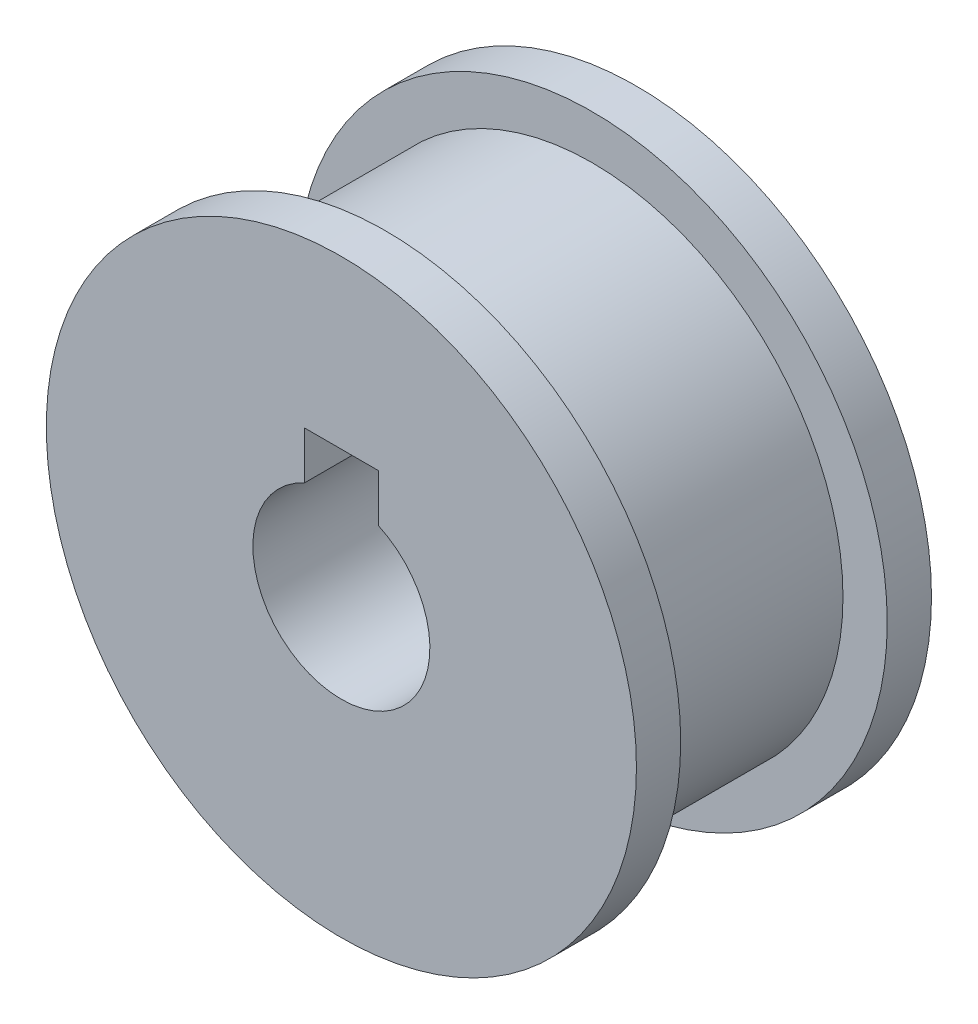
SolidWorks part; units mm, degrees
ref_plane "前视基准面" through (0, 0, 0) normal (0, 0, 1) x (1, 0, 0)
ref_plane "上视基准面" through (0, 0, 0) normal (0, 1, 0) x (1, 0, 0)
ref_plane "右视基准面" through (0, 0, 0) normal (1, 0, 0) x (0, 0, -1)
other "Configuration Table"
sketch "草图1" plane through (0, 0, 0) normal (0, 0, 1) x (1, 0, 0)
  circle A0 centre (0, 0) radius 17
  dimension "D1" = 34
extrude "凸台-拉伸1" add sketch "草图1" along normal mid plane 20
sketch "草图2" plane through (0, 0, 10) normal (0, 0, 1) x (1, 0, 0)
  circle A0 centre (0, 0) radius 20
  dimension "D1" = 40
extrude "凸台-拉伸2" add sketch "草图2" against normal blind 3
mirror "镜向1" about plane through (0, 0, 0) normal (0, 0, 1) of "凸台-拉伸2"
sketch "草图3" plane through (0, 0, 10) normal (0, 0, 1) x (1, 0, 0)
  line L0 (0, 0) -> (0, 10.1969) construction
  line L1 (2.5, 8.68) -> (-2.5, 8.68)
  line L2 (-2.5, 8.68) -> (-2.5, 5.4544)
  line L3 (2.5, 8.68) -> (2.5, 5.4544)
  arc A0 (-2.5, 5.4544) -> (2.5, 5.4544) centre (0, 0) ccw
  point P8 (0, 8.68)
  dimension "D1" = 12
  dimension "D2" = 8.68
  dimension "D3" = 2.5
extrude "切除-拉伸1" cut sketch "草图3" against normal through all
